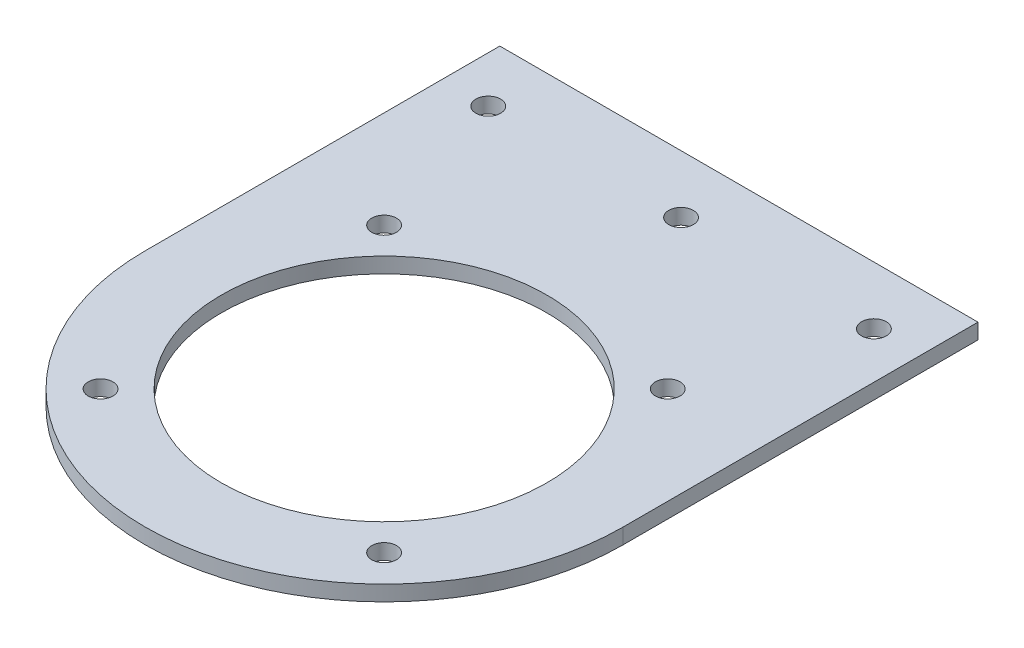
SolidWorks part; units mm, degrees
material "Thornel Mat VMA"
ref_plane "前视基准面" through (0, 0, 0) normal (0, 0, 1) x (1, 0, 0)
ref_plane "上视基准面" through (0, 0, 0) normal (0, 1, 0) x (1, 0, 0)
ref_plane "右视基准面" through (0, 0, 0) normal (1, 0, 0) x (0, 0, -1)
sketch "草图1" plane through (0, 0, 0) normal (0, 1, 0) x (1, 0, 0)
  line L0 (-31, 0) -> (-31, 31)
  line L1 (-31, 31) -> (31, 31) construction
  line L2 (31, 31) -> (31, 0)
  line L3 (-31, 31) -> (-31, 46)
  line L4 (-31, 46) -> (31, 46)
  line L5 (31, 46) -> (31, 31)
  line L6 (-31, 38.5) -> (-25, 38.5) construction
  line L7 (-25, 38.5) -> (0, 38.5) construction
  line L8 (0, 38.5) -> (25, 38.5) construction
  line L9 (25, 38.5) -> (31, 38.5) construction
  line L10 (0, 0) -> (0, 26) construction
  line L11 (0, 0) -> (18.3848, 18.3848) construction
  circle A0 centre (0, 0) radius 31
  circle A1 centre (0, 0) radius 21.1
  circle A2 centre (0, 0) radius 13.1
  circle A3 centre (0, 0) radius 17.5 construction
  circle A4 centre (0, 17.5) radius 2.1
  circle A5 centre (-17.5, 0) radius 2.1
  circle A6 centre (0, -17.5) radius 2.1
  circle A7 centre (17.5, 0) radius 2.1
  circle A8 centre (-25, 38.5) radius 1.6
  circle A9 centre (0, 38.5) radius 1.6
  circle A10 centre (25, 38.5) radius 1.6
  circle A11 centre (0, 0) radius 26 construction
  circle A12 centre (18.3848, 18.3848) radius 1.6
  circle A13 centre (18.3848, -18.3848) radius 1.6
  circle A14 centre (-18.3848, -18.3848) radius 1.6
  circle A15 centre (-18.3848, 18.3848) radius 1.6
  dimension "D3" = 42.2
  dimension "D4" = 26.2
  dimension "D5" = 35
  dimension "D6" = 4.2
  dimension "D8" = 3.2
  dimension "D9" = 52
  dimension "D1" = 31
  dimension "D2" = 15
  dimension "D7" = 6
  dimension "D10" = 45
  dimension "D11" = 4
extrude "凸台-拉伸1" add sketch "草图1" along normal blind 2 contours A0 L2 L5 L4 L3 L0 A10 A9 A8 | A0 A15 A14 A13 A12 A1
